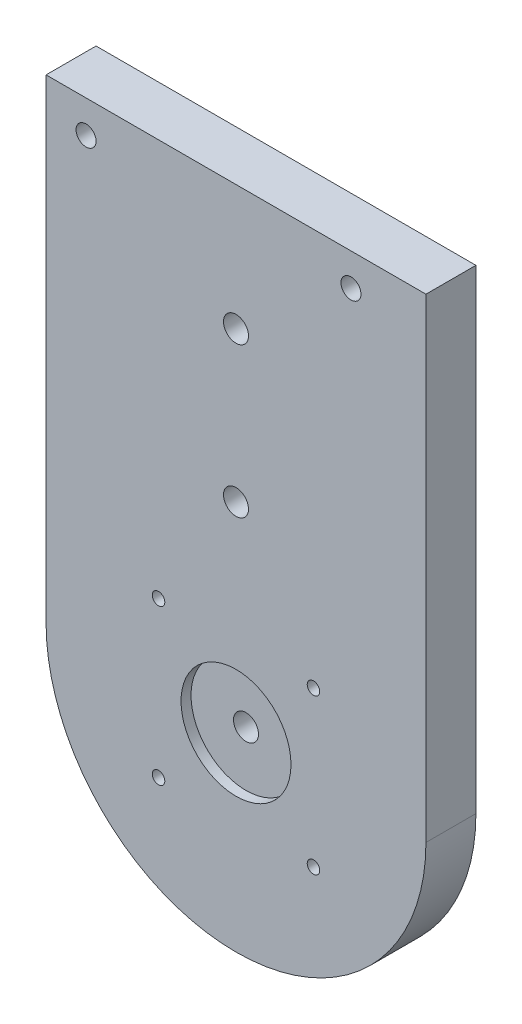
SolidWorks part; units mm, degrees
material "PTEG"
ref_plane "Alzado" through (0, 0, 0) normal (0, 0, 1) x (1, 0, 0)
ref_plane "Planta" through (0, 0, 0) normal (0, 1, 0) x (1, 0, 0)
ref_plane "Vista lateral" through (0, 0, 0) normal (1, 0, 0) x (0, 0, -1)
sketch "Croquis1" plane through (0, 0, 0) normal (0, 0, 1) x (1, 0, 0)
  line L0 (-38, 0) -> (-38, 95)
  line L1 (38, 0) -> (38, 95)
  line L2 (-38, 95) -> (38, 95)
  line L3 (0, 0) -> (0, 15.5) construction
  arc A0 (-38, 0) -> (38, 0) centre (0, 0) ccw
  circle A2 centre (0, 40) radius 2.5
  circle A3 centre (0, 0) radius 2.5
  circle A4 centre (0, 70) radius 2.5
  circle A5 centre (-15.5, 15.5) radius 1.25
  circle A6 centre (15.5, 15.5) radius 1.25
  circle A7 centre (15.5, -15.5) radius 1.25
  circle A8 centre (-15.5, -15.5) radius 1.25
  dimension "D2" = 70
  dimension "D3" = 5
  dimension "D5" = 5
  dimension "D6" = 5
  dimension "D9" = 2.5
  dimension "D1" = 76
  dimension "D4" = 40
  dimension "D7" = 95
  dimension "D8" = 15.5
  dimension "D10" = 15.5
  dimension "D11" = 2
  dimension "D12" = 2
extrude "Saliente-Extruir1" add sketch "Croquis1" along normal blind 10
sketch "Croquis3" plane through (0, 0, 10) normal (0, 0, 1) x (1, 0, 0)
  circle A0 centre (0, 0) radius 11
  dimension "D1" = 22
extrude "Cortar-Extruir1" cut sketch "Croquis3" against normal blind 2
sketch "Croquis4" plane through (0, 0, 10) normal (0, 0, 1) x (1, 0, 0)
  line L0 (-38, 95) -> (-38, 0) construction
  line L1 (38, 95) -> (-38, 95) construction
  line L2 (38, 0) -> (38, 95) construction
  circle A0 centre (-30, 88.5) radius 2
  circle A1 centre (23, 88.5) radius 2
  point P6 (0, 0)
  dimension "D2" = 4
  dimension "D1" = 8
  dimension "D3" = 6.5
  dimension "D4" = 15
extrude "Cortar-Extruir2" cut sketch "Croquis4" against normal through all
